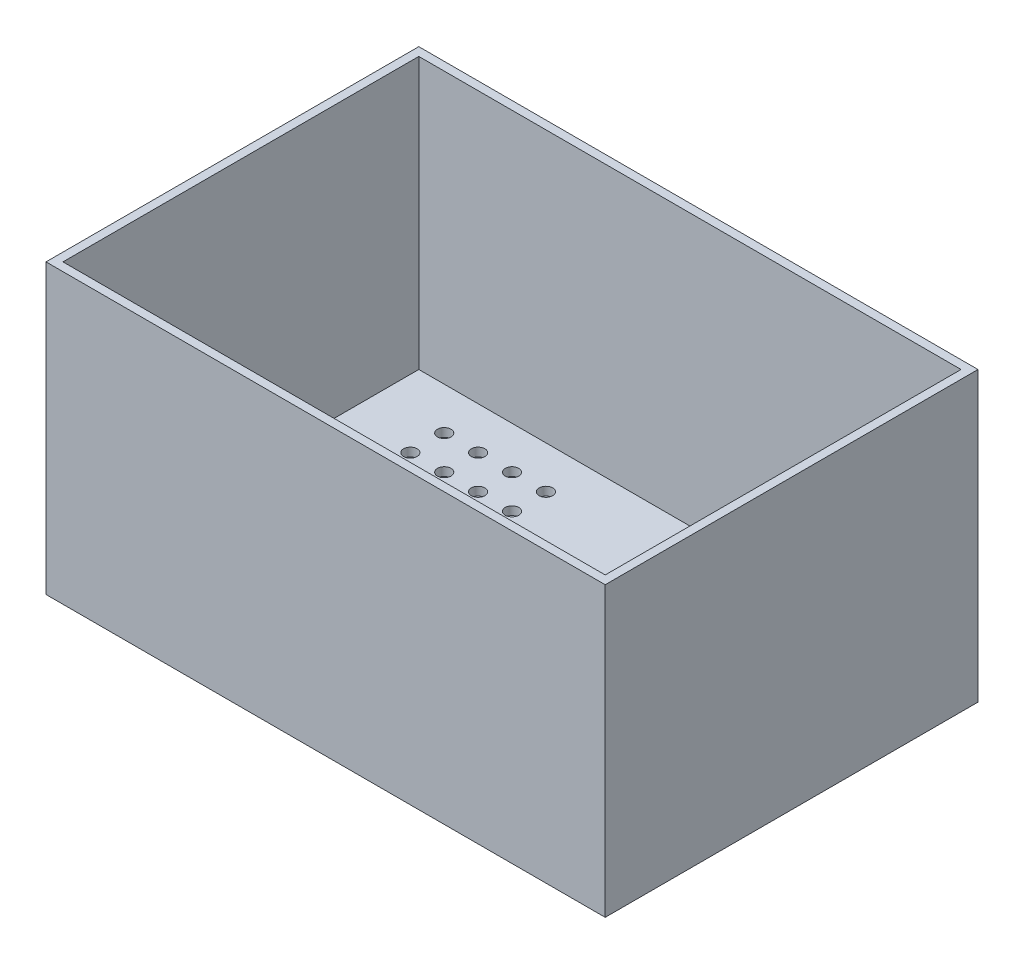
SolidWorks part; units mm, degrees
material "Glass"
ref_plane "Front Plane" through (0, 0, 0) normal (0, 0, 1) x (1, 0, 0)
ref_plane "Top Plane" through (0, 0, 0) normal (0, 1, 0) x (1, 0, 0)
ref_plane "Right Plane" through (0, 0, 0) normal (1, 0, 0) x (0, 0, -1)
sketch "Sketch1" plane through (0, 0, 0) normal (0, 1, 0) x (1, 0, 0)
  line L1 (-101.6, -66.675) -> (101.6, -66.675)
  line L2 (-101.6, -66.675) -> (-101.6, 66.675)
  line L3 (-101.6, 66.675) -> (101.6, 66.675)
  line L4 (101.6, -66.675) -> (101.6, 66.675)
  line L5 (-101.6, -66.675) -> (101.6, 66.675) construction
  line L6 (-101.6, 66.675) -> (101.6, -66.675) construction
  line L7 (-104.775, -69.85) -> (104.775, -69.85)
  line L8 (-104.775, -69.85) -> (-104.775, 69.85)
  line L9 (-104.775, 69.85) -> (104.775, 69.85)
  line L10 (104.775, -69.85) -> (104.775, 69.85)
  line L11 (-104.775, -69.85) -> (104.775, 69.85) construction
  line L12 (-104.775, 69.85) -> (104.775, -69.85) construction
  point P0 (0, 0)
  point P6 (0, 0)
  dimension "D1" = 3.175
  dimension "D2" = 3.175
  dimension "D3" = 203.2
  dimension "D4" = 133.35
extrude "Boss-Extrude1" add sketch "Sketch1" along normal blind 101.6
sketch "Sketch2" plane through (0, 0, 0) normal (0, 1, 0) x (1, 0, 0)
  line L1 (-104.775, 69.85) -> (104.775, 69.85)
  line L2 (-104.775, 69.85) -> (-104.775, -69.85)
  line L3 (-104.775, -69.85) -> (104.775, -69.85)
  line L4 (104.775, 69.85) -> (104.775, -69.85)
extrude "Boss-Extrude2" add sketch "Sketch2" against normal blind 3.175
sketch "Sketch3" plane through (0, 0, 0) normal (0, 1, 0) x (1, 0, 0)
  circle A0 centre (-76.2, 50.8) radius 2.54
  circle A1 centre (-63.5, 50.8) radius 2.54
  circle A2 centre (-50.8, 50.8) radius 2.54
  circle A3 centre (-38.1, 50.8) radius 2.54
  circle A4 centre (-63.5, 38.1) radius 2.54
  circle A5 centre (-50.8, 38.1) radius 2.54
  circle A6 centre (-38.1, 38.1) radius 2.54
  circle A7 centre (-63.5, 25.4) radius 2.54
  circle A8 centre (-50.8, 25.4) radius 2.54
  circle A9 centre (-38.1, 25.4) radius 2.54
  circle A10 centre (-63.5, 12.7) radius 2.54
  circle A11 centre (-50.8, 12.7) radius 2.54
  circle A12 centre (-38.1, 12.7) radius 2.54
  circle A13 centre (-63.5, 0) radius 2.54
  circle A14 centre (-50.8, 0) radius 2.54
  circle A15 centre (-38.1, 0) radius 2.54
  circle A16 centre (-63.5, -12.7) radius 2.54
  circle A17 centre (-50.8, -12.7) radius 2.54
  circle A18 centre (-38.1, -12.7) radius 2.54
  circle A19 centre (-63.5, -25.4) radius 2.54
  circle A20 centre (-50.8, -25.4) radius 2.54
  circle A21 centre (-38.1, -25.4) radius 2.54
  circle A22 centre (-63.5, -38.1) radius 2.54
  circle A23 centre (-50.8, -38.1) radius 2.54
  circle A24 centre (-38.1, -38.1) radius 2.54
  circle A25 centre (-63.5, -50.8) radius 2.54
  circle A26 centre (-50.8, -50.8) radius 2.54
  circle A27 centre (-38.1, -50.8) radius 2.54
  circle A28 centre (-76.2, 38.1) radius 2.54
  circle A29 centre (-76.2, 25.4) radius 2.54
  circle A30 centre (-76.2, 12.7) radius 2.54
  circle A31 centre (-76.2, 0) radius 2.54
  circle A32 centre (-76.2, -12.7) radius 2.54
  circle A33 centre (-76.2, -25.4) radius 2.54
  circle A34 centre (-76.2, -38.1) radius 2.54
  circle A35 centre (-76.2, -50.8) radius 2.54
  dimension "D1" = 5.08
  dimension "D2" = 50.8
  dimension "D3" = 76.2
  dimension "D4" = 4
  dimension "D5" = 9
extrude "Cut-Extrude1" cut sketch "Sketch3" against normal through all
sketch "Sketch4" plane through (0, -3.175, 0) normal (0, -1, 0) x (1, 0, 0)
  line L1 (-104.775, 69.85) -> (104.775, 69.85)
  line L2 (-104.775, 69.85) -> (-104.775, -69.85)
  line L3 (-104.775, -69.85) -> (104.775, -69.85)
  line L4 (104.775, 69.85) -> (104.775, -69.85)
extrude "Boss-Extrude3" add sketch "Sketch4" along normal blind 3.175
